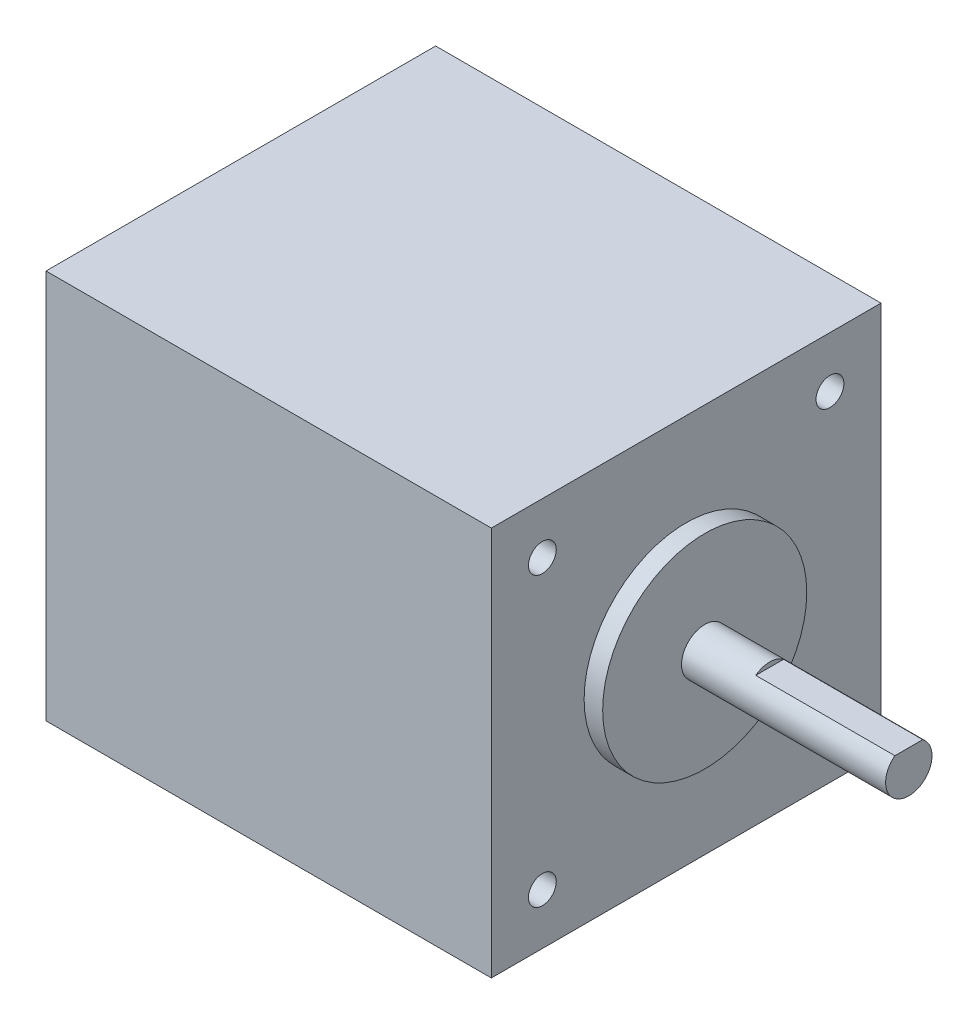
SolidWorks part; units mm, degrees
ref_plane "Front Plane" through (0, 0, 0) normal (0, 0, 1) x (1, 0, 0)
ref_plane "Top Plane" through (0, 0, 0) normal (0, 1, 0) x (1, 0, 0)
ref_plane "Right Plane" through (0, 0, 0) normal (1, 0, 0) x (0, 0, -1)
sketch "Sketch1" plane through (0, 0, 0) normal (1, 0, 0) x (0, 0, -1)
  line L1 (0, 0) -> (42, 0)
  line L2 (0, 0) -> (0, 42)
  line L3 (0, 42) -> (42, 42)
  line L4 (42, 0) -> (42, 42)
  dimension "D1" = 42
  dimension "D2" = 42
extrude "Boss-Extrude1" add sketch "Sketch1" along normal blind 48
sketch "Sketch2" plane through (48, 0, 0) normal (1, 0, 0) x (0, 0, -1)
  line L0 (42, 42) -> (0, 0) construction
  line L1 (0, 0) -> (0, 42) construction
  line L3 (42, 0) -> (0, 42) construction
  circle A0 centre (21, 21) radius 18
  dimension "D1" = 36
ref_plane "Plane2" through (0, 21, 0) normal (0, 1, 0) x (1, 0, 0)
ref_plane "Plane3" through (0, 23, 0) normal (0, 1, 0) x (1, 0, 0)
sketch "Sketch3" plane through (48, 0, 0) normal (1, 0, 0) x (0, 0, -1)
  circle A0 centre (21, 21) radius 11
  dimension "D1" = 22
extrude "Boss-Extrude2" add sketch "Sketch3" along normal blind 2
sketch "Sketch4" plane through (50, 0, 0) normal (1, 0, 0) x (0, 0, -1)
  circle A0 centre (21, 21) radius 2.5
  circle A1 centre (21, 21) radius 11 construction
  dimension "D1" = 5
extrude "Boss-Extrude3" add sketch "Sketch4" along normal blind 22
sketch "Sketch5" plane through (0, 23, 0) normal (0, 1, 0) x (1, 0, 0)
  line L0 (72, 18.5) -> (72, 23.5) construction
  line L1 (57, 25.5022) -> (72, 25.5022)
  line L2 (57, 25.5022) -> (57, 15.8752)
  line L3 (57, 15.8752) -> (72, 15.8752)
  line L4 (72, 25.5022) -> (72, 15.8752)
  dimension "D1" = 15
extrude "Cut-Extrude1" cut sketch "Sketch5" along normal blind 2
sketch "Sketch6" plane through (48, 0, 0) normal (1, 0, 0) x (0, 0, -1)
  line L0 (42, 0) -> (0, 42) construction
  line L1 (5.5, 36.5) -> (36.5, 36.5)
  line L2 (5.5, 36.5) -> (5.5, 5.5)
  line L3 (5.5, 5.5) -> (36.5, 5.5)
  line L4 (36.5, 36.5) -> (36.5, 5.5)
  line L5 (42, 42) -> (0, 0) construction
  circle A0 centre (5.5, 36.5) radius 1.5
  circle A1 centre (36.5, 36.5) radius 1.5
  circle A2 centre (36.5, 5.5) radius 1.5
  circle A3 centre (5.5, 5.5) radius 1.5
  dimension "D2" = 3
  dimension "D3" = 3
  dimension "D4" = 3
  dimension "D5" = 3
  dimension "D1" = 31
extrude "Cut-Extrude2" cut sketch "Sketch6" against normal blind 4.5 contours L1 A0 L2 | L2 A0 L1 | L4 A1 L1 | L1 A1 L4 | L3 A2 L4 | L4 A2 L3 | L2 A3 L3 | L3 A3 L2
chamfer "Chamfer1" [suppressed] distance 5 angle 45
